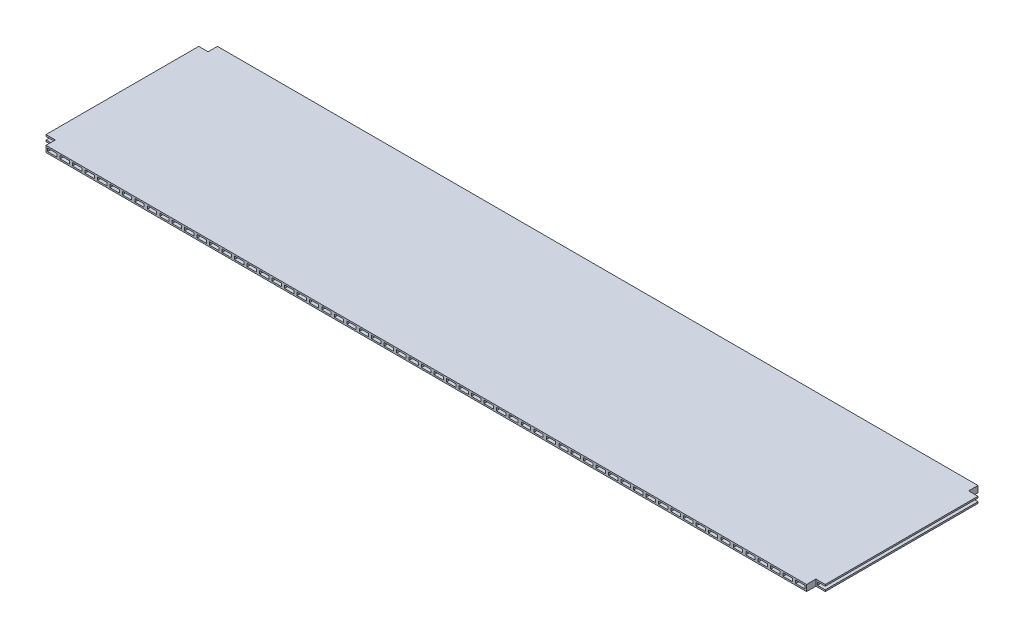
SolidWorks part; units mm, degrees
ref_plane "前视基准面" through (0, 0, 0) normal (0, 0, 1) x (1, 0, 0)
ref_plane "上视基准面" through (0, 0, 0) normal (0, 1, 0) x (1, 0, 0)
ref_plane "右视基准面" through (0, 0, 0) normal (1, 0, 0) x (0, 0, -1)
other "Configuration Table"
sketch "草图1" plane through (0, 0, 0) normal (0, 1, 0) x (1, 0, 0)
  line L1 (-250, 110) -> (250, 110)
  line L2 (-250, 110) -> (-250, 0)
  line L3 (-250, 0) -> (250, 0)
  line L4 (250, 110) -> (250, 0)
  point P4 (0, 0)
  dimension "D1" = 500
  dimension "D2" = 110
extrude "凸台-拉伸1" add sketch "草图1" along normal blind 4
sketch "草图2" plane through (0, 0, -110) normal (0, 0, -1) x (-1, 0, 0)
  line L0 (-59, 3) -> (-59, 1)
  line L5 (-59, 3) -> (-53, 3)
  line L6 (-53, 3) -> (-53, 1)
  line L7 (-250, 0) -> (250, 0) construction
  line L8 (-3, 3) -> (3, 3)
  line L9 (-3, 3) -> (-3, 1)
  line L10 (-3, 1) -> (3, 1)
  line L11 (3, 3) -> (3, 1)
  line L12 (-250, 4) -> (250, 4) construction
  line L13 (5, 3) -> (5, 1)
  line L14 (5, 3) -> (11, 3)
  line L15 (11, 3) -> (11, 1)
  line L16 (5, 1) -> (11, 1)
  line L17 (13, 3) -> (13, 1)
  line L18 (13, 3) -> (19, 3)
  line L19 (19, 3) -> (19, 1)
  line L20 (13, 1) -> (19, 1)
  line L21 (21, 3) -> (21, 1)
  line L22 (21, 3) -> (27, 3)
  line L23 (27, 3) -> (27, 1)
  line L24 (21, 1) -> (27, 1)
  line L25 (29, 3) -> (29, 1)
  line L26 (29, 3) -> (35, 3)
  line L27 (35, 3) -> (35, 1)
  line L28 (29, 1) -> (35, 1)
  line L29 (37, 3) -> (37, 1)
  line L30 (37, 3) -> (43, 3)
  line L31 (43, 3) -> (43, 1)
  line L32 (37, 1) -> (43, 1)
  line L33 (45, 3) -> (45, 1)
  line L34 (45, 3) -> (51, 3)
  line L35 (51, 3) -> (51, 1)
  line L36 (45, 1) -> (51, 1)
  line L37 (-11, 3) -> (-11, 1)
  line L38 (-11, 3) -> (-5, 3)
  line L39 (-5, 3) -> (-5, 1)
  line L40 (-11, 1) -> (-5, 1)
  line L41 (-19, 3) -> (-19, 1)
  line L42 (-19, 3) -> (-13, 3)
  line L43 (-13, 3) -> (-13, 1)
  line L44 (-19, 1) -> (-13, 1)
  line L45 (-27, 3) -> (-27, 1)
  line L46 (-27, 3) -> (-21, 3)
  line L47 (-21, 3) -> (-21, 1)
  line L48 (-27, 1) -> (-21, 1)
  line L49 (-35, 3) -> (-35, 1)
  line L50 (-35, 3) -> (-29, 3)
  line L51 (-29, 3) -> (-29, 1)
  line L52 (-35, 1) -> (-29, 1)
  line L53 (-43, 3) -> (-43, 1)
  line L54 (-43, 3) -> (-37, 3)
  line L55 (-37, 3) -> (-37, 1)
  line L56 (-43, 1) -> (-37, 1)
  line L57 (-51, 3) -> (-51, 1)
  line L58 (-51, 3) -> (-45, 3)
  line L59 (-45, 3) -> (-45, 1)
  line L60 (-51, 1) -> (-45, 1)
  line L61 (-59, 1) -> (-53, 1)
  line L62 (-67, 3) -> (-67, 1)
  line L63 (-67, 3) -> (-61, 3)
  line L64 (-61, 3) -> (-61, 1)
  line L65 (-67, 1) -> (-61, 1)
  line L66 (-75, 3) -> (-75, 1)
  line L67 (-75, 3) -> (-69, 3)
  line L68 (-69, 3) -> (-69, 1)
  line L69 (-75, 1) -> (-69, 1)
  line L70 (-83, 3) -> (-83, 1)
  line L71 (-83, 3) -> (-77, 3)
  line L72 (-77, 3) -> (-77, 1)
  line L73 (-83, 1) -> (-77, 1)
  line L74 (-91, 3) -> (-91, 1)
  line L75 (-91, 3) -> (-85, 3)
  line L76 (-85, 3) -> (-85, 1)
  line L77 (-91, 1) -> (-85, 1)
  line L78 (-99, 3) -> (-99, 1)
  line L79 (-99, 3) -> (-93, 3)
  line L80 (-93, 3) -> (-93, 1)
  line L81 (-99, 1) -> (-93, 1)
  line L82 (-107, 3) -> (-107, 1)
  line L83 (-107, 3) -> (-101, 3)
  line L84 (-101, 3) -> (-101, 1)
  line L85 (-107, 1) -> (-101, 1)
  line L86 (-115, 3) -> (-115, 1)
  line L87 (-115, 3) -> (-109, 3)
  line L88 (-109, 3) -> (-109, 1)
  line L89 (-115, 1) -> (-109, 1)
  line L90 (-123, 3) -> (-123, 1)
  line L91 (-123, 3) -> (-117, 3)
  line L92 (-117, 3) -> (-117, 1)
  line L93 (-123, 1) -> (-117, 1)
  line L94 (-131, 3) -> (-131, 1)
  line L95 (-131, 3) -> (-125, 3)
  line L96 (-125, 3) -> (-125, 1)
  line L97 (-131, 1) -> (-125, 1)
  line L98 (-139, 3) -> (-139, 1)
  line L99 (-139, 3) -> (-133, 3)
  line L100 (-133, 3) -> (-133, 1)
  line L101 (-139, 1) -> (-133, 1)
  line L102 (-147, 3) -> (-147, 1)
  line L103 (-147, 3) -> (-141, 3)
  line L104 (-141, 3) -> (-141, 1)
  line L105 (-147, 1) -> (-141, 1)
  line L106 (-155, 3) -> (-155, 1)
  line L107 (-155, 3) -> (-149, 3)
  line L108 (-149, 3) -> (-149, 1)
  line L109 (-155, 1) -> (-149, 1)
  line L110 (-163, 3) -> (-163, 1)
  line L111 (-163, 3) -> (-157, 3)
  line L112 (-157, 3) -> (-157, 1)
  line L113 (-163, 1) -> (-157, 1)
  line L114 (-171, 3) -> (-171, 1)
  line L115 (-171, 3) -> (-165, 3)
  line L116 (-165, 3) -> (-165, 1)
  line L117 (-171, 1) -> (-165, 1)
  line L118 (-179, 3) -> (-179, 1)
  line L119 (-179, 3) -> (-173, 3)
  line L120 (-173, 3) -> (-173, 1)
  line L121 (-179, 1) -> (-173, 1)
  line L122 (-187, 3) -> (-187, 1)
  line L123 (-187, 3) -> (-181, 3)
  line L124 (-181, 3) -> (-181, 1)
  line L125 (-187, 1) -> (-181, 1)
  line L126 (-195, 3) -> (-195, 1)
  line L127 (-195, 3) -> (-189, 3)
  line L128 (-189, 3) -> (-189, 1)
  line L129 (-195, 1) -> (-189, 1)
  line L130 (-203, 3) -> (-203, 1)
  line L131 (-203, 3) -> (-197, 3)
  line L132 (-197, 3) -> (-197, 1)
  line L133 (-203, 1) -> (-197, 1)
  line L134 (-211, 3) -> (-211, 1)
  line L135 (-211, 3) -> (-205, 3)
  line L136 (-205, 3) -> (-205, 1)
  line L137 (-211, 1) -> (-205, 1)
  line L138 (-219, 3) -> (-219, 1)
  line L139 (-219, 3) -> (-213, 3)
  line L140 (-213, 3) -> (-213, 1)
  line L141 (-219, 1) -> (-213, 1)
  line L142 (-227, 3) -> (-227, 1)
  line L143 (-227, 3) -> (-221, 3)
  line L144 (-221, 3) -> (-221, 1)
  line L145 (-227, 1) -> (-221, 1)
  line L146 (-235, 3) -> (-235, 1)
  line L147 (-235, 3) -> (-229, 3)
  line L148 (-229, 3) -> (-229, 1)
  line L149 (-235, 1) -> (-229, 1)
  line L150 (-243, 3) -> (-243, 1)
  line L151 (-243, 3) -> (-237, 3)
  line L152 (-237, 3) -> (-237, 1)
  line L153 (-243, 1) -> (-237, 1)
  line L154 (-251, 3) -> (-251, 1)
  line L155 (-251, 3) -> (-245, 3)
  line L156 (-245, 3) -> (-245, 1)
  line L157 (-251, 1) -> (-245, 1)
  line L158 (-259, 3) -> (-259, 1)
  line L159 (-259, 3) -> (-253, 3)
  line L160 (-253, 3) -> (-253, 1)
  line L161 (-259, 1) -> (-253, 1)
  line L162 (-267, 3) -> (-267, 1)
  line L163 (-267, 3) -> (-261, 3)
  line L164 (-261, 3) -> (-261, 1)
  line L165 (-267, 1) -> (-261, 1)
  line L166 (-275, 3) -> (-275, 1)
  line L167 (-275, 3) -> (-269, 3)
  line L168 (-269, 3) -> (-269, 1)
  line L169 (-275, 1) -> (-269, 1)
  line L170 (-283, 3) -> (-283, 1)
  line L171 (-283, 3) -> (-277, 3)
  line L172 (-277, 3) -> (-277, 1)
  line L173 (-283, 1) -> (-277, 1)
  line L174 (-291, 3) -> (-291, 1)
  line L175 (-291, 3) -> (-285, 3)
  line L176 (-285, 3) -> (-285, 1)
  line L177 (-291, 1) -> (-285, 1)
  line L178 (-299, 3) -> (-299, 1)
  line L179 (-299, 3) -> (-293, 3)
  line L180 (-293, 3) -> (-293, 1)
  line L181 (-299, 1) -> (-293, 1)
  line L182 (-307, 3) -> (-307, 1)
  line L183 (-307, 3) -> (-301, 3)
  line L184 (-301, 3) -> (-301, 1)
  line L185 (-307, 1) -> (-301, 1)
  line L186 (-315, 3) -> (-315, 1)
  line L187 (-315, 3) -> (-309, 3)
  line L188 (-309, 3) -> (-309, 1)
  line L189 (-315, 1) -> (-309, 1)
  line L190 (53, 3) -> (53, 1)
  line L191 (53, 3) -> (59, 3)
  line L192 (59, 3) -> (59, 1)
  line L193 (53, 1) -> (59, 1)
  line L194 (61, 3) -> (61, 1)
  line L195 (61, 3) -> (67, 3)
  line L196 (67, 3) -> (67, 1)
  line L197 (61, 1) -> (67, 1)
  line L198 (69, 3) -> (69, 1)
  line L199 (69, 3) -> (75, 3)
  line L200 (75, 3) -> (75, 1)
  line L201 (69, 1) -> (75, 1)
  line L202 (77, 3) -> (77, 1)
  line L203 (77, 3) -> (83, 3)
  line L204 (83, 3) -> (83, 1)
  line L205 (77, 1) -> (83, 1)
  line L206 (85, 3) -> (85, 1)
  line L207 (85, 3) -> (91, 3)
  line L208 (91, 3) -> (91, 1)
  line L209 (85, 1) -> (91, 1)
  line L210 (93, 3) -> (93, 1)
  line L211 (93, 3) -> (99, 3)
  line L212 (99, 3) -> (99, 1)
  line L213 (93, 1) -> (99, 1)
  line L214 (101, 3) -> (101, 1)
  line L215 (101, 3) -> (107, 3)
  line L216 (107, 3) -> (107, 1)
  line L217 (101, 1) -> (107, 1)
  line L218 (109, 3) -> (109, 1)
  line L219 (109, 3) -> (115, 3)
  line L220 (115, 3) -> (115, 1)
  line L221 (109, 1) -> (115, 1)
  line L222 (117, 3) -> (117, 1)
  line L223 (117, 3) -> (123, 3)
  line L224 (123, 3) -> (123, 1)
  line L225 (117, 1) -> (123, 1)
  line L226 (125, 3) -> (125, 1)
  line L227 (125, 3) -> (131, 3)
  line L228 (131, 3) -> (131, 1)
  line L229 (125, 1) -> (131, 1)
  line L230 (133, 3) -> (133, 1)
  line L231 (133, 3) -> (139, 3)
  line L232 (139, 3) -> (139, 1)
  line L233 (133, 1) -> (139, 1)
  line L234 (141, 3) -> (141, 1)
  line L235 (141, 3) -> (147, 3)
  line L236 (147, 3) -> (147, 1)
  line L237 (141, 1) -> (147, 1)
  line L238 (149, 3) -> (149, 1)
  line L239 (149, 3) -> (155, 3)
  line L240 (155, 3) -> (155, 1)
  line L241 (149, 1) -> (155, 1)
  line L242 (157, 3) -> (157, 1)
  line L243 (157, 3) -> (163, 3)
  line L244 (163, 3) -> (163, 1)
  line L245 (157, 1) -> (163, 1)
  line L246 (165, 3) -> (165, 1)
  line L247 (165, 3) -> (171, 3)
  line L248 (171, 3) -> (171, 1)
  line L249 (165, 1) -> (171, 1)
  line L250 (173, 3) -> (173, 1)
  line L251 (173, 3) -> (179, 3)
  line L252 (179, 3) -> (179, 1)
  line L253 (173, 1) -> (179, 1)
  line L254 (181, 3) -> (181, 1)
  line L255 (181, 3) -> (187, 3)
  line L256 (187, 3) -> (187, 1)
  line L257 (181, 1) -> (187, 1)
  line L258 (189, 3) -> (189, 1)
  line L259 (189, 3) -> (195, 3)
  line L260 (195, 3) -> (195, 1)
  line L261 (189, 1) -> (195, 1)
  line L262 (197, 3) -> (197, 1)
  line L263 (197, 3) -> (203, 3)
  line L264 (203, 3) -> (203, 1)
  line L265 (197, 1) -> (203, 1)
  line L266 (205, 3) -> (205, 1)
  line L267 (205, 3) -> (211, 3)
  line L268 (211, 3) -> (211, 1)
  line L269 (205, 1) -> (211, 1)
  line L270 (213, 3) -> (213, 1)
  line L271 (213, 3) -> (219, 3)
  line L272 (219, 3) -> (219, 1)
  line L273 (213, 1) -> (219, 1)
  line L274 (221, 3) -> (221, 1)
  line L275 (221, 3) -> (227, 3)
  line L276 (227, 3) -> (227, 1)
  line L277 (221, 1) -> (227, 1)
  line L278 (229, 3) -> (229, 1)
  line L279 (229, 3) -> (235, 3)
  line L280 (235, 3) -> (235, 1)
  line L281 (229, 1) -> (235, 1)
  line L282 (237, 3) -> (237, 1)
  line L283 (237, 3) -> (243, 3)
  line L284 (243, 3) -> (243, 1)
  line L285 (237, 1) -> (243, 1)
  line L286 (245, 3) -> (245, 1)
  line L287 (245, 3) -> (251, 3)
  line L288 (251, 3) -> (251, 1)
  line L289 (245, 1) -> (251, 1)
  line L290 (253, 3) -> (253, 1)
  line L291 (253, 3) -> (259, 3)
  line L292 (259, 3) -> (259, 1)
  line L293 (253, 1) -> (259, 1)
  line L294 (261, 3) -> (261, 1)
  line L295 (261, 3) -> (267, 3)
  line L296 (267, 3) -> (267, 1)
  line L297 (261, 1) -> (267, 1)
  line L298 (269, 3) -> (269, 1)
  line L299 (269, 3) -> (275, 3)
  line L300 (275, 3) -> (275, 1)
  line L301 (269, 1) -> (275, 1)
  line L302 (277, 3) -> (277, 1)
  line L303 (277, 3) -> (283, 3)
  line L304 (283, 3) -> (283, 1)
  line L305 (277, 1) -> (283, 1)
  line L306 (285, 3) -> (285, 1)
  line L307 (285, 3) -> (291, 3)
  line L308 (291, 3) -> (291, 1)
  line L309 (285, 1) -> (291, 1)
  line L310 (293, 3) -> (293, 1)
  line L311 (293, 3) -> (299, 3)
  line L312 (299, 3) -> (299, 1)
  line L313 (293, 1) -> (299, 1)
  line L314 (301, 3) -> (301, 1)
  line L315 (301, 3) -> (307, 3)
  line L316 (307, 3) -> (307, 1)
  line L317 (301, 1) -> (307, 1)
  line L318 (309, 3) -> (309, 1)
  line L319 (309, 3) -> (315, 3)
  line L320 (315, 3) -> (315, 1)
  line L321 (309, 1) -> (315, 1)
  point P4 (0, 1)
  dimension "D1" = 1
  dimension "D2" = 1
  dimension "D3" = 6
  dimension "D4" = 40
  dimension "D5" = 40
extrude "切除-拉伸1" cut sketch "草图2" against normal through all both and the other way through all
sketch "草图3" plane through (0, 0, 0) normal (0, -1, 0) x (1, 0, 0)
  line L0 (-250, 0) -> (250, 0) construction
  line L1 (250, 0) -> (244, 0)
  line L2 (250, 0) -> (250, -6)
  line L3 (250, -6) -> (244, -6)
  line L4 (244, 0) -> (244, -6)
  line L5 (250, -110) -> (244, -110)
  line L6 (250, -110) -> (250, -104)
  line L7 (250, -104) -> (244, -104)
  line L8 (244, -110) -> (244, -104)
  line L9 (-250, 0) -> (-244, 0)
  line L10 (-250, 0) -> (-250, -6)
  line L11 (-250, -6) -> (-244, -6)
  line L12 (-244, 0) -> (-244, -6)
  line L13 (-250, -110) -> (-244, -110)
  line L14 (-250, -110) -> (-250, -104)
  line L15 (-250, -104) -> (-244, -104)
  line L16 (-244, -110) -> (-244, -104)
  dimension "D1" = 6
extrude "切除-拉伸2" cut sketch "草图3" against normal through all both and the other way through all
